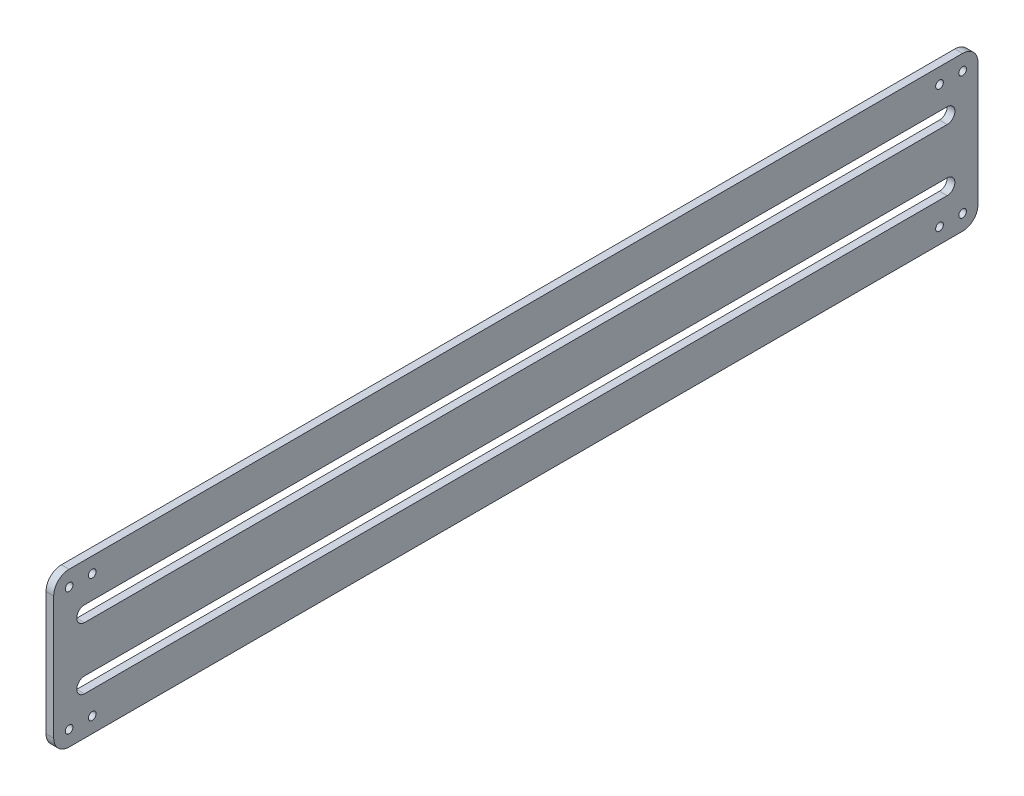
SolidWorks part; units mm, degrees
ref_plane "Front Plane" through (0, 0, 0) normal (0, 0, 1) x (1, 0, 0)
ref_plane "Top Plane" through (0, 0, 0) normal (0, 1, 0) x (1, 0, 0)
ref_plane "Right Plane" through (0, 0, 0) normal (1, 0, 0) x (0, 0, -1)
sketch "Sketch1" plane through (0, 0, 0) normal (1, 0, 0) x (0, 0, -1)
  line L1 (-184.15, -31.75) -> (184.15, -31.75)
  line L2 (-190.5, -25.4) -> (-190.5, 25.4)
  line L3 (-184.15, 31.75) -> (184.15, 31.75)
  line L4 (190.5, -25.4) -> (190.5, 25.4)
  line L5 (-190.5, -31.75) -> (190.5, 31.75) construction
  line L6 (-190.5, 31.75) -> (190.5, -31.75) construction
  arc A0 (184.15, 31.75) -> (190.5, 25.4) centre (184.15, 25.4) cw
  arc A1 (190.5, -25.4) -> (184.15, -31.75) centre (184.15, -25.4) cw
  arc A2 (-184.15, -31.75) -> (-190.5, -25.4) centre (-184.15, -25.4) cw
  arc A3 (-190.5, 25.4) -> (-184.15, 31.75) centre (-184.15, 25.4) cw
  point P0 (0, 0)
  dimension "D3" = 6.35
  dimension "D1" = 381
  dimension "D2" = 63.5
extrude "Outer Cut" add sketch "Sketch1" along normal mid plane 3.175
sketch "Sketch2" plane through (1.5875, 0, 0) normal (1, 0, 0) x (0, 0, -1)
  line L0 (-190.5, 0) -> (190.5, 0) construction
  line L1 (-190.5, 25.4) -> (-190.5, -25.4) construction
  line L2 (190.5, -25.4) -> (190.5, 25.4) construction
  line L3 (-177.8, 12.7) -> (177.8, 12.7) construction
  line L4 (-177.8, 15.875) -> (177.8, 15.875)
  line L5 (-177.8, 9.525) -> (177.8, 9.525)
  line L6 (-177.8, -12.7) -> (177.8, -12.7) construction
  line L7 (-177.8, -15.875) -> (177.8, -15.875)
  line L8 (-177.8, -9.525) -> (177.8, -9.525)
  arc A0 (-177.8, 15.875) -> (-177.8, 9.525) centre (-177.8, 12.7) ccw
  arc A1 (177.8, 9.525) -> (177.8, 15.875) centre (177.8, 12.7) ccw
  arc A2 (-177.8, -15.875) -> (-177.8, -9.525) centre (-177.8, -12.7) cw
  arc A3 (177.8, -9.525) -> (177.8, -15.875) centre (177.8, -12.7) cw
  point P2 (0, 12.7)
  point P16 (0, -12.7)
  dimension "D1" = 6.35
  dimension "D2" = 25.4
  dimension "D3" = 12.7
  dimension "D4" = 12.7
extrude "Slots" cut sketch "Sketch2" against normal through all
sketch "Sketch3" plane through (1.5875, 0, 0) normal (1, 0, 0) x (0, 0, -1)
  line L0 (-190.5, 25.4) -> (-190.5, -25.4) construction
  line L1 (184.15, 31.75) -> (-184.15, 31.75) construction
  line L2 (0, 0) -> (0, 31.75) construction
  line L3 (0, 0) -> (-190.5, 0) construction
  circle A0 centre (-184.15, 25.4) radius 1.5875
  circle A1 centre (-174.625, 25.4) radius 1.5875
  circle A2 centre (-174.625, -25.4) radius 1.5875
  circle A3 centre (-184.15, -25.4) radius 1.5875
  circle A4 centre (174.625, 25.4) radius 1.5875
  circle A5 centre (184.15, 25.4) radius 1.5875
  circle A6 centre (184.15, -25.4) radius 1.5875
  circle A7 centre (174.625, -25.4) radius 1.5875
  dimension "D1" = 3.175
  dimension "D2" = 6.35
  dimension "D3" = 6.35
  dimension "D5" = 9.525
  dimension "D4" = 2
extrude "Mount Holes" cut sketch "Sketch3" against normal through all
